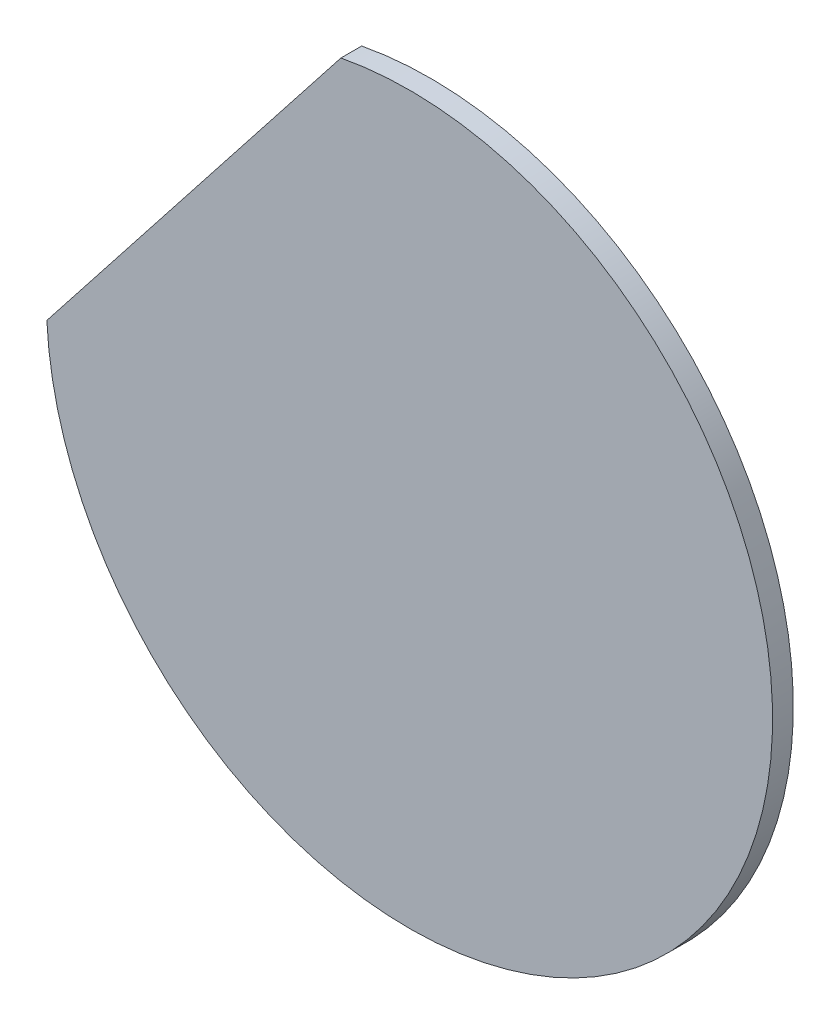
SolidWorks part; units mm, degrees
ref_plane "Front Plane" through (0, 0, 0) normal (0, 0, 1) x (1, 0, 0)
ref_plane "Top Plane" through (0, 0, 0) normal (0, 1, 0) x (1, 0, 0)
ref_plane "Right Plane" through (0, 0, 0) normal (1, 0, 0) x (0, 0, -1)
sketch "Sketch2" plane through (0, 0, 0) normal (0, 0, 1) x (1, 0, 0)
  line L0 (-33.0593, 171.849) -> (-174.7909, -8.5516)
  circle A0 centre (0, 0) radius 175
  dimension "D1" = 350
extrude "Boss-Extrude1" add sketch "Sketch2" along normal blind 10 contours L0 A0
